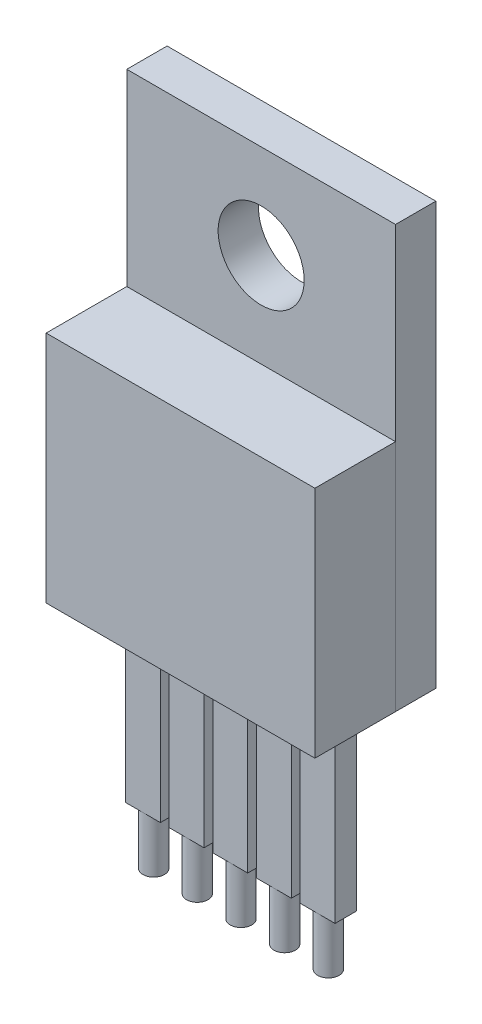
SolidWorks part; units mm, degrees
ref_plane "Front" through (0, 0, 0) normal (0, 0, 1) x (1, 0, 0)
ref_plane "Top" through (0, 0, 0) normal (0, 1, 0) x (1, 0, 0)
ref_plane "Right" through (0, 0, 0) normal (1, 0, 0) x (0, 0, -1)
sketch "Sketch1" plane through (0, 0, 0) normal (0, 0, 1) x (1, 0, 0)
  line L0 (0, 0) -> (0, 3.5) construction
  line L1 (-5, 3.5) -> (5, 3.5)
  line L2 (-5, 3.5) -> (-5, -12.2)
  line L3 (-5, -12.2) -> (5, -12.2)
  line L4 (5, 3.5) -> (5, -12.2)
  circle A0 centre (0, 0) radius 1.6
  dimension "D1" = 3.2
  dimension "D2" = 3.5
  dimension "D3" = 15.7
  dimension "D4" = 10
extrude "Boss-Extrude1" add sketch "Sketch1" along normal blind 1.5
sketch "Sketch2" plane through (0, 0, 1.5) normal (0, 0, 1) x (1, 0, 0)
  line L0 (-5, 3.5) -> (-5, -12.2) construction
  line L1 (-5, -3.5) -> (5, -3.5)
  line L2 (-5, -3.5) -> (-5, -12.2)
  line L3 (-5, -12.2) -> (5, -12.2)
  line L4 (5, -3.5) -> (5, -12.2)
  dimension "D1" = 8.7
extrude "Boss-Extrude2" add sketch "Sketch2" along normal blind 3
sketch "Sketch3" plane through (5, 0, 0) normal (1, 0, 0) x (0, 0, -1)
  line L0 (-1.5, -3.5) -> (-1.5, -12.2)
  line L1 (-4.5, -12.2) -> (0, -12.2) construction
split line "Split Line1"
sketch "Sketch4" plane through (0, -12.2, 0) normal (0, -1, 0) x (1, 0, 0)
  line L0 (0, 0) -> (0, 3.8585) construction
  line L1 (-3.9, 2.65) -> (-2.6, 2.65)
  line L2 (-3.9, 2.65) -> (-3.9, 1.85)
  line L3 (-3.9, 1.85) -> (-2.6, 1.85)
  line L4 (-2.6, 2.65) -> (-2.6, 1.85)
  line L6 (-3.9, 2.25) -> (-0.704, 2.25) construction
  line L7 (-5, 0) -> (5, 0) construction
  line L8 (-2.275, 2.65) -> (-2.275, 1.85)
  line L9 (-2.275, 2.65) -> (-0.975, 2.65)
  line L10 (-0.975, 2.65) -> (-0.975, 1.85)
  line L11 (-2.275, 1.85) -> (-0.975, 1.85)
  line L12 (-0.65, 2.65) -> (-0.65, 1.85)
  line L13 (-0.65, 2.65) -> (0.65, 2.65)
  line L14 (0.65, 2.65) -> (0.65, 1.85)
  line L15 (-0.65, 1.85) -> (0.65, 1.85)
  line L16 (0.975, 2.65) -> (0.975, 1.85)
  line L17 (0.975, 2.65) -> (2.275, 2.65)
  line L18 (2.275, 2.65) -> (2.275, 1.85)
  line L19 (0.975, 1.85) -> (2.275, 1.85)
  line L20 (2.6, 2.65) -> (2.6, 1.85)
  line L21 (2.6, 2.65) -> (3.9, 2.65)
  line L22 (3.9, 2.65) -> (3.9, 1.85)
  line L23 (2.6, 1.85) -> (3.9, 1.85)
  dimension "D1" = 2.25
  dimension "D2" = 0.8
  dimension "D4" = 6.5
  dimension "D5" = 1.3
  dimension "D3" = 5
extrude "Boss-Extrude3" add sketch "Sketch4" along normal blind 6.8
sketch "Sketch5" plane through (0, -19, 0) normal (0, -1, 0) x (1, 0, 0)
  line L0 (-2.6, 2.65) -> (-3.9, 2.65) construction
  line L1 (-3.9, 1.85) -> (-2.6, 1.85) construction
  line L2 (-3.25, 2.65) -> (-3.25, 1.85) construction
  line L3 (3.25, 2.65) -> (3.25, 1.85) construction
  line L4 (3.9, 2.65) -> (2.6, 2.65) construction
  line L5 (2.6, 1.85) -> (3.9, 1.85) construction
  circle A0 centre (-3.25, 2.25) radius 0.4
  circle A1 centre (-1.625, 2.25) radius 0.4
  circle A2 centre (0, 2.25) radius 0.4
  circle A3 centre (1.625, 2.25) radius 0.4
  circle A4 centre (3.25, 2.25) radius 0.4
  dimension "D1" = 5
extrude "Boss-Extrude4" add sketch "Sketch5" along normal blind 2
